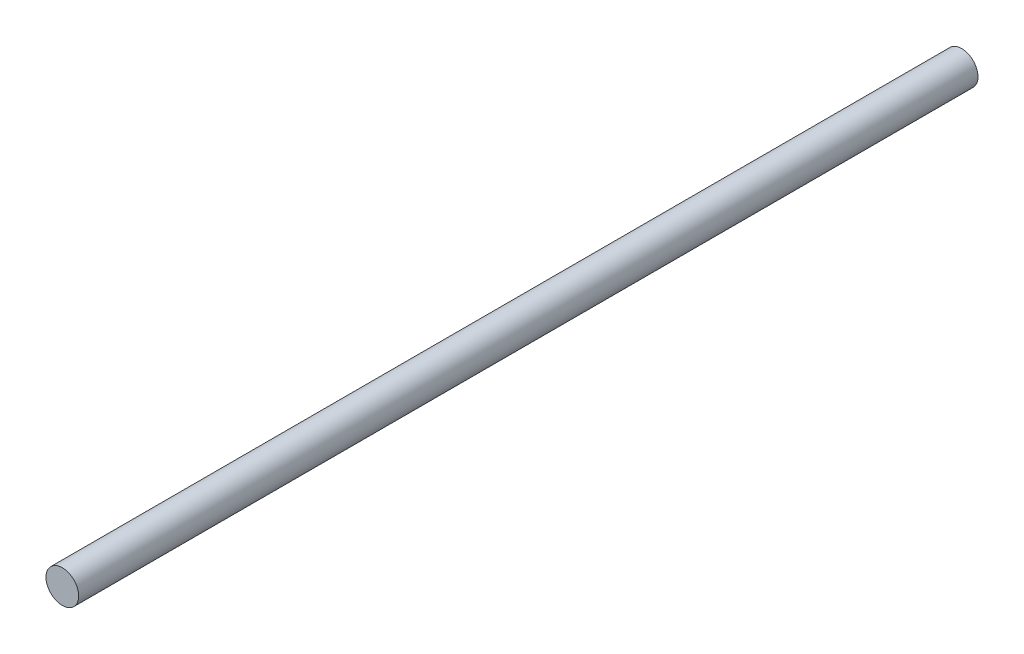
SolidWorks part; units mm, degrees
ref_plane "Front Plane" through (0, 0, 0) normal (1, 0, 0) x (0, 1, 0)
ref_plane "Top Plane" through (0, 0, 0) normal (0, 0, 1) x (0, 1, 0)
ref_plane "Right Plane" through (0, 0, 0) normal (0, 1, 0) x (-1, 0, 0)
sketch "Sketch1" plane through (0, 0, 0) normal (0, 0, 1) x (0, 1, 0)
  circle A0 centre (0, 0) radius 4
  dimension "D1" = 8
extrude "Boss-Extrude1" add sketch "Sketch1" along normal blind 220
